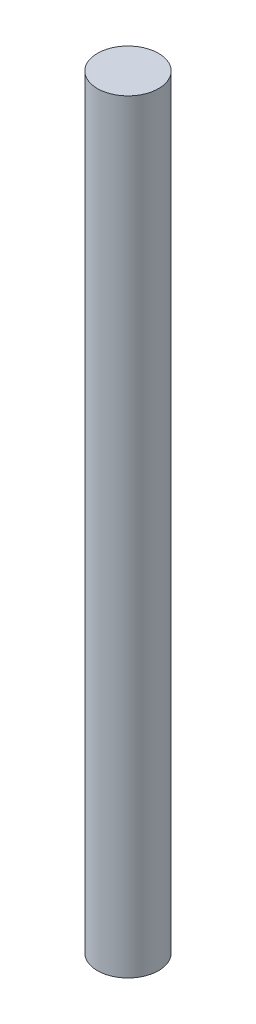
SolidWorks part; units mm, degrees
ref_plane "Front Plane" through (0, 0, 0) normal (0, 0, 1) x (1, 0, 0)
ref_plane "Top Plane" through (0, 0, 0) normal (0, 1, 0) x (1, 0, 0)
ref_plane "Right Plane" through (0, 0, 0) normal (1, 0, 0) x (0, 0, -1)
sketch "Sketch1" plane through (0, 0, 0) normal (0, 1, 0) x (1, 0, 0)
  circle A0 centre (0, 0) radius 6
  dimension "D1" = 12
extrude "Boss-Extrude1" add sketch "Sketch1" along normal blind 150
